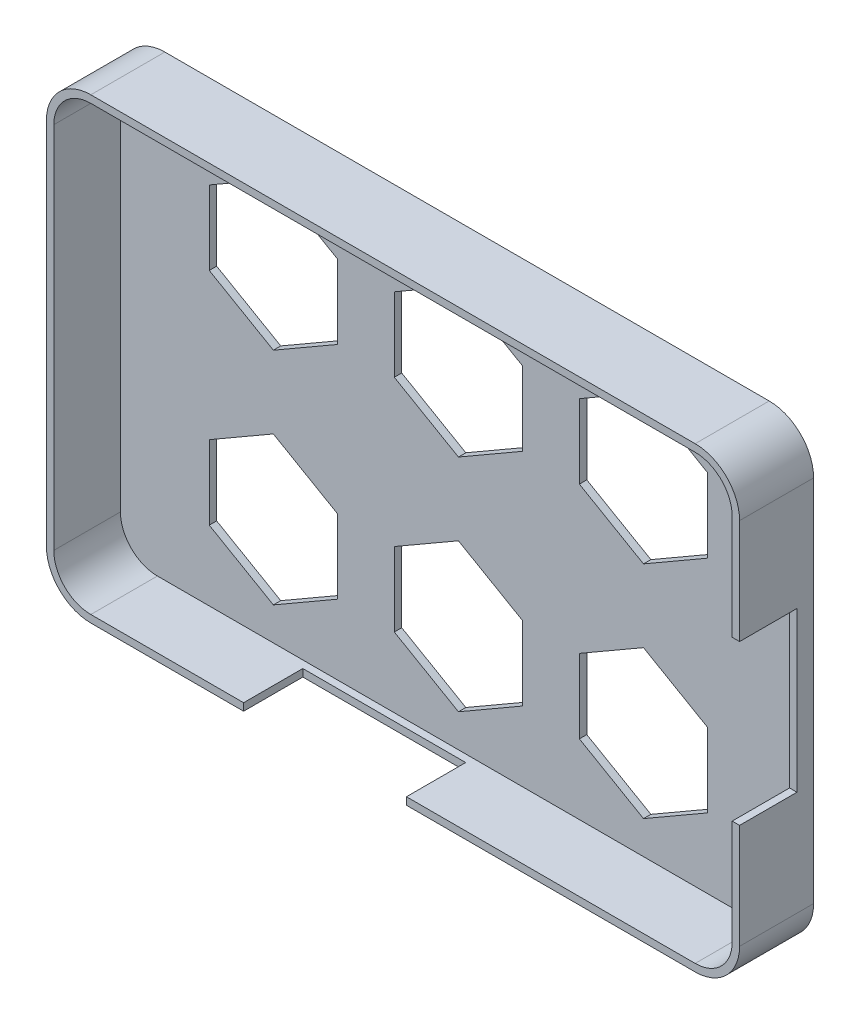
SolidWorks part; units mm, degrees
ref_plane "Ebene vorne" through (0, 0, 0) normal (1, 0, 0) x (0, 1, 0)
ref_plane "Ebene oben" through (0, 0, 0) normal (0, 0, 1) x (0, 1, 0)
ref_plane "Ebene rechts" through (0, 0, 0) normal (0, 1, 0) x (-1, 0, 0)
sketch "Skizze1" plane through (0, 0, 0) normal (0, 0, 1) x (0, 1, 0)
  line L0 (-30.9, -46.82) -> (30.9, -46.82)
  line L1 (-30.9, -46.82) -> (-30.9, 46.82)
  line L2 (-30.9, 46.82) -> (30.9, 46.82)
  line L3 (30.9, -46.82) -> (30.9, 46.82)
  line L4 (-30.9, -46.82) -> (30.9, 46.82) construction
  line L5 (-30.9, 46.82) -> (30.9, -46.82) construction
  point P0 (0, 0)
  dimension "D1" = 61.8
  dimension "D2" = 93.64
extrude "Aufsatz-Linear austragen1" add sketch "Skizze1" along normal blind 10
fillet "Verrundung1" radius 6 4 edges at (46.82, -30.9, 5) (-46.82, -30.9, 5) (-46.82, 30.9, 5) (46.82, 30.9, 5)
shell "Wandung1" thickness 1
sketch "Skizze2" plane through (46.82, 0, 0) normal (1, 0, 0) x (0, 1, 0)
  line L0 (-24.9, 10) -> (24.9, 10) construction
  line L1 (-10.75, 17.75) -> (10.75, 17.75)
  line L2 (-10.75, 17.75) -> (-10.75, 2.25)
  line L3 (-10.75, 2.25) -> (10.75, 2.25)
  line L4 (10.75, 17.75) -> (10.75, 2.25)
  line L5 (-10.75, 17.75) -> (10.75, 2.25) construction
  line L6 (-10.75, 2.25) -> (10.75, 17.75) construction
  point P0 (0, 10)
  dimension "D1" = 21.5
  dimension "D2" = 15.5
extrude "Schnitt-Linear austragen1" cut sketch "Skizze2" against normal blind 6
sketch "Skizze3" plane through (0, -30.9, 0) normal (0, -1, 0) x (1, 0, 0)
  line L0 (-40.82, 10) -> (40.82, 10) construction
  line L1 (1.82, 10) -> (-20.18, 10)
  line L2 (1.82, 10) -> (1.82, 2)
  line L3 (1.82, 2) -> (-20.18, 2)
  line L4 (-20.18, 10) -> (-20.18, 2)
  dimension "D1" = 22
  dimension "D2" = 8
  dimension "D3" = 39
extrude "Schnitt-Linear austragen2" cut sketch "Skizze3" against normal blind 6
sketch "Skizze4" plane through (0, 0, 0) normal (0, 0, -1) x (1, 0, 0)
  line L0 (-33.82, 30.9) -> (-33.82, -30.9) construction
  line L2 (-25.1597, 25.45) -> (-33.82, 20.45)
  line L3 (-33.82, 20.45) -> (-33.82, 10.45)
  line L4 (-33.82, 10.45) -> (-25.1597, 5.45)
  line L5 (-25.1597, 5.45) -> (-16.4995, 10.45)
  line L6 (-16.4995, 10.45) -> (-16.4995, 20.45)
  line L7 (-16.4995, 20.45) -> (-25.1597, 25.45)
  line L8 (-25.1597, -4.35) -> (-33.82, -9.35)
  line L9 (-33.82, -9.35) -> (-33.82, -19.35)
  line L10 (-33.82, -19.35) -> (-25.1597, -24.35)
  line L11 (-25.1597, -24.35) -> (-16.4995, -19.35)
  line L12 (-16.4995, -19.35) -> (-16.4995, -9.35)
  line L13 (-16.4995, -9.35) -> (-25.1597, -4.35)
  line L14 (-46.82, -24.9) -> (-46.82, 24.9) construction
  circle A8 centre (-25.1597, 15.45) radius 8.6603 construction
  dimension "D3" = 10.45
  dimension "D4" = 2
  dimension "D5" = 13
  dimension "D1" = 10
  dimension "D2" = 61.8
extrude "Schnitt-Linear austragen4" cut sketch "Skizze4" against normal blind 6
pattern_linear "Lineares Muster1" count 3 spacing 25 along (1, 0, 0) of "Schnitt-Linear austragen4"
